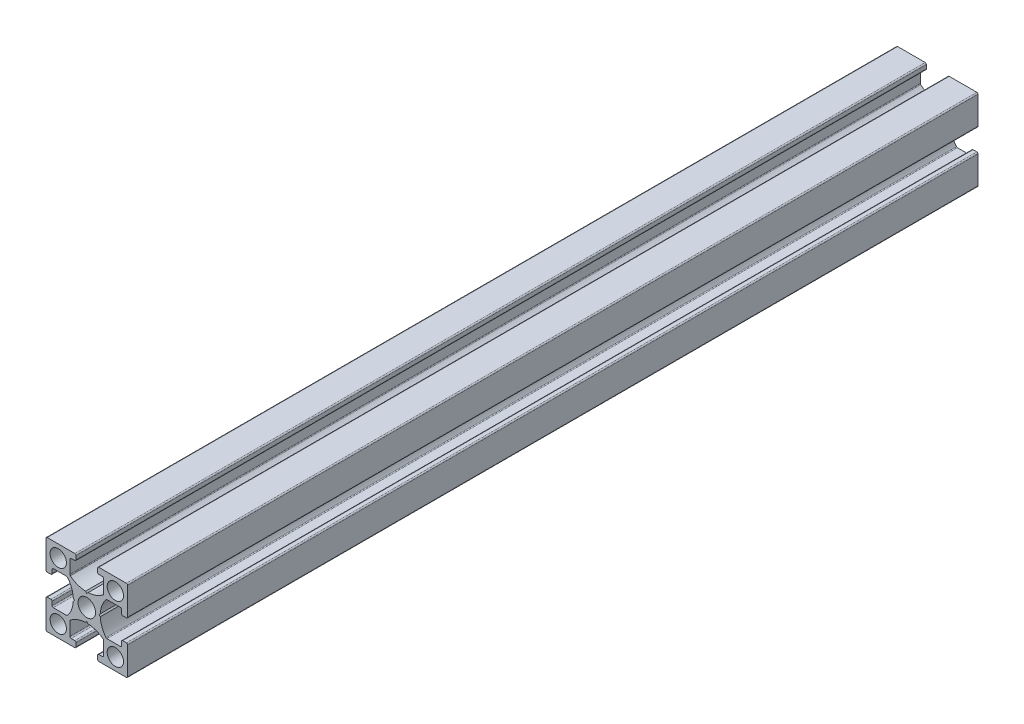
SolidWorks part; units mm, degrees
ref_plane "정면" through (0, 0, 0) normal (0, 0, 1) x (1, 0, 0)
ref_plane "윗면" through (0, 0, 0) normal (0, 1, 0) x (1, 0, 0)
ref_plane "우측면" through (0, 0, 0) normal (1, 0, 0) x (0, 0, -1)
sketch "Model" plane through (0, 0, 0) normal (0, 0, 1) x (1, 0, 0)
  line L0 (2292.4151, 1187.1915) -> (2314.8128, 1187.1915) construction
  line L1 (2307.7639, 1192.1343) -> (2307.7639, 1195.3915)
  line L2 (2307.4639, 1195.6915) -> (2306.5639, 1195.6915)
  line L3 (2306.2639, 1195.9915) -> (2306.2639, 1196.8915)
  line L4 (2306.5639, 1197.1915) -> (2313.3139, 1197.1915)
  line L5 (2313.6139, 1196.8915) -> (2313.6139, 1190.1415)
  line L6 (2313.3139, 1189.8415) -> (2312.4139, 1189.8415)
  line L7 (2312.1139, 1190.1415) -> (2312.1139, 1191.0415)
  line L8 (2311.8139, 1191.3415) -> (2308.5567, 1191.3415)
  line L9 (2306.9212, 1187.4988) -> (2306.6139, 1187.1915)
  line L10 (2306.6139, 1187.1915) -> (2306.9212, 1186.8843)
  line L11 (2308.5567, 1183.0415) -> (2311.8139, 1183.0415)
  line L12 (2312.1139, 1183.3415) -> (2312.1139, 1184.2415)
  line L13 (2312.4139, 1184.5415) -> (2313.3139, 1184.5415)
  line L14 (2313.6139, 1184.2415) -> (2313.6139, 1177.4915)
  line L15 (2313.3139, 1177.1915) -> (2306.5639, 1177.1915)
  line L16 (2306.2639, 1177.4915) -> (2306.2639, 1178.3915)
  line L17 (2306.5639, 1178.6915) -> (2307.4639, 1178.6915)
  line L18 (2307.7639, 1178.9915) -> (2307.7639, 1182.2488)
  line L19 (2303.9212, 1183.8843) -> (2303.6139, 1184.1915)
  line L20 (2303.6139, 1184.1915) -> (2303.3066, 1183.8843)
  line L21 (2299.4639, 1182.2488) -> (2299.4639, 1178.9915)
  line L22 (2299.7639, 1178.6915) -> (2300.6639, 1178.6915)
  line L23 (2300.9639, 1178.3915) -> (2300.9639, 1177.4915)
  line L24 (2300.6639, 1177.1915) -> (2293.9139, 1177.1915)
  line L25 (2293.6139, 1177.4915) -> (2293.6139, 1184.2415)
  line L26 (2293.9139, 1184.5415) -> (2294.8139, 1184.5415)
  line L27 (2295.1139, 1184.2415) -> (2295.1139, 1183.3415)
  line L28 (2295.4139, 1183.0415) -> (2298.6712, 1183.0415)
  line L29 (2300.3066, 1186.8843) -> (2300.6139, 1187.1915)
  line L30 (2300.6139, 1187.1915) -> (2300.3066, 1187.4988)
  line L31 (2298.6712, 1191.3415) -> (2295.4139, 1191.3415)
  line L32 (2295.1139, 1191.0415) -> (2295.1139, 1190.1415)
  line L33 (2294.8139, 1189.8415) -> (2293.9139, 1189.8415)
  line L34 (2293.6139, 1190.1415) -> (2293.6139, 1196.8915)
  line L35 (2293.9139, 1197.1915) -> (2300.6639, 1197.1915)
  line L36 (2300.9639, 1196.8915) -> (2300.9639, 1195.9915)
  line L37 (2300.6639, 1195.6915) -> (2299.7639, 1195.6915)
  line L38 (2299.4639, 1195.3915) -> (2299.4639, 1192.1343)
  line L39 (2303.3066, 1190.4988) -> (2303.6139, 1190.1915)
  line L40 (2303.6139, 1190.1915) -> (2303.9212, 1190.4988)
  line L41 (2294.1139, 1194.1915) -> (2299.1139, 1194.1915) construction
  line L42 (2296.6139, 1196.6915) -> (2296.6139, 1191.6915) construction
  line L43 (2294.1139, 1180.1915) -> (2299.1139, 1180.1915) construction
  line L44 (2296.6139, 1177.6915) -> (2296.6139, 1182.6915) construction
  line L45 (2303.6139, 1198.3904) -> (2303.6139, 1175.9927) construction
  line L46 (2313.1139, 1194.1915) -> (2308.1139, 1194.1915) construction
  line L47 (2310.6139, 1196.6915) -> (2310.6139, 1191.6915) construction
  line L48 (2310.6139, 1177.6915) -> (2310.6139, 1182.6915) construction
  line L49 (2313.1139, 1180.1915) -> (2308.1139, 1180.1915) construction
  circle A0 centre (2303.6139, 1187.1915) radius 2.15
  circle A1 centre (2296.6139, 1194.1915) radius 2
  circle A2 centre (2296.6139, 1180.1915) radius 2
  circle A3 centre (2310.6139, 1194.1915) radius 2
  circle A4 centre (2310.6139, 1180.1915) radius 2
  arc A5 (2307.7639, 1195.3915) -> (2307.4639, 1195.6915) centre (2307.4639, 1195.3915) ccw
  arc A6 (2306.2639, 1195.9915) -> (2306.5639, 1195.6915) centre (2306.5639, 1195.9915) ccw
  arc A7 (2306.5639, 1197.1915) -> (2306.2639, 1196.8915) centre (2306.5639, 1196.8915) ccw
  arc A8 (2313.6139, 1196.8915) -> (2313.3139, 1197.1915) centre (2313.3139, 1196.8915) ccw
  arc A9 (2313.3139, 1189.8415) -> (2313.6139, 1190.1415) centre (2313.3139, 1190.1415) ccw
  arc A10 (2312.1139, 1190.1415) -> (2312.4139, 1189.8415) centre (2312.4139, 1190.1415) ccw
  arc A11 (2312.1139, 1191.0415) -> (2311.8139, 1191.3415) centre (2311.8139, 1191.0415) ccw
  arc A12 (2308.5567, 1191.3415) -> (2308.3217, 1191.2281) centre (2308.5567, 1191.0415) ccw
  arc A13 (2308.3217, 1191.2281) -> (2306.9212, 1187.4988) centre (2313.4048, 1187.1915) ccw
  arc A14 (2306.9212, 1186.8843) -> (2308.3217, 1183.155) centre (2313.4048, 1187.1915) ccw
  arc A15 (2308.3217, 1183.155) -> (2308.5567, 1183.0415) centre (2308.5567, 1183.3415) ccw
  arc A16 (2311.8139, 1183.0415) -> (2312.1139, 1183.3415) centre (2311.8139, 1183.3415) ccw
  arc A17 (2312.4139, 1184.5415) -> (2312.1139, 1184.2415) centre (2312.4139, 1184.2415) ccw
  arc A18 (2313.6139, 1184.2415) -> (2313.3139, 1184.5415) centre (2313.3139, 1184.2415) ccw
  arc A19 (2313.3139, 1177.1915) -> (2313.6139, 1177.4915) centre (2313.3139, 1177.4915) ccw
  arc A20 (2306.2639, 1177.4915) -> (2306.5639, 1177.1915) centre (2306.5639, 1177.4915) ccw
  arc A21 (2306.5639, 1178.6915) -> (2306.2639, 1178.3915) centre (2306.5639, 1178.3915) ccw
  arc A22 (2307.4639, 1178.6915) -> (2307.7639, 1178.9915) centre (2307.4639, 1178.9915) ccw
  arc A23 (2307.7639, 1182.2488) -> (2307.6505, 1182.4837) centre (2307.4639, 1182.2488) ccw
  arc A24 (2307.6505, 1182.4837) -> (2303.9212, 1183.8843) centre (2303.6139, 1177.4007) ccw
  arc A25 (2303.3066, 1183.8843) -> (2299.5774, 1182.4837) centre (2303.6139, 1177.4007) ccw
  arc A26 (2299.5774, 1182.4837) -> (2299.4639, 1182.2488) centre (2299.7639, 1182.2488) ccw
  arc A27 (2299.4639, 1178.9915) -> (2299.7639, 1178.6915) centre (2299.7639, 1178.9915) ccw
  arc A28 (2300.9639, 1178.3915) -> (2300.6639, 1178.6915) centre (2300.6639, 1178.3915) ccw
  arc A29 (2300.6639, 1177.1915) -> (2300.9639, 1177.4915) centre (2300.6639, 1177.4915) ccw
  arc A30 (2293.6139, 1177.4915) -> (2293.9139, 1177.1915) centre (2293.9139, 1177.4915) ccw
  arc A31 (2293.9139, 1184.5415) -> (2293.6139, 1184.2415) centre (2293.9139, 1184.2415) ccw
  arc A32 (2295.1139, 1184.2415) -> (2294.8139, 1184.5415) centre (2294.8139, 1184.2415) ccw
  arc A33 (2295.1139, 1183.3415) -> (2295.4139, 1183.0415) centre (2295.4139, 1183.3415) ccw
  arc A34 (2298.6712, 1183.0415) -> (2298.9061, 1183.155) centre (2298.6712, 1183.3415) ccw
  arc A35 (2298.9061, 1183.155) -> (2300.3066, 1186.8843) centre (2293.8231, 1187.1915) ccw
  arc A36 (2300.3066, 1187.4988) -> (2298.9061, 1191.2281) centre (2293.8231, 1187.1915) ccw
  arc A37 (2298.9061, 1191.2281) -> (2298.6712, 1191.3415) centre (2298.6712, 1191.0415) ccw
  arc A38 (2295.4139, 1191.3415) -> (2295.1139, 1191.0415) centre (2295.4139, 1191.0415) ccw
  arc A39 (2294.8139, 1189.8415) -> (2295.1139, 1190.1415) centre (2294.8139, 1190.1415) ccw
  arc A40 (2293.6139, 1190.1415) -> (2293.9139, 1189.8415) centre (2293.9139, 1190.1415) ccw
  arc A41 (2293.9139, 1197.1915) -> (2293.6139, 1196.8915) centre (2293.9139, 1196.8915) ccw
  arc A42 (2300.9639, 1196.8915) -> (2300.6639, 1197.1915) centre (2300.6639, 1196.8915) ccw
  arc A43 (2300.6639, 1195.6915) -> (2300.9639, 1195.9915) centre (2300.6639, 1195.9915) ccw
  arc A44 (2299.7639, 1195.6915) -> (2299.4639, 1195.3915) centre (2299.7639, 1195.3915) ccw
  arc A45 (2299.4639, 1192.1343) -> (2299.5774, 1191.8994) centre (2299.7639, 1192.1343) ccw
  arc A46 (2299.5774, 1191.8994) -> (2303.3066, 1190.4988) centre (2303.6139, 1196.9824) ccw
  arc A47 (2303.9212, 1190.4988) -> (2307.6505, 1191.8994) centre (2303.6139, 1196.9824) ccw
  arc A48 (2307.6505, 1191.8994) -> (2307.7639, 1192.1343) centre (2307.4639, 1192.1343) ccw
extrude "보스-돌출1" add sketch "Model" along normal blind 208.5
